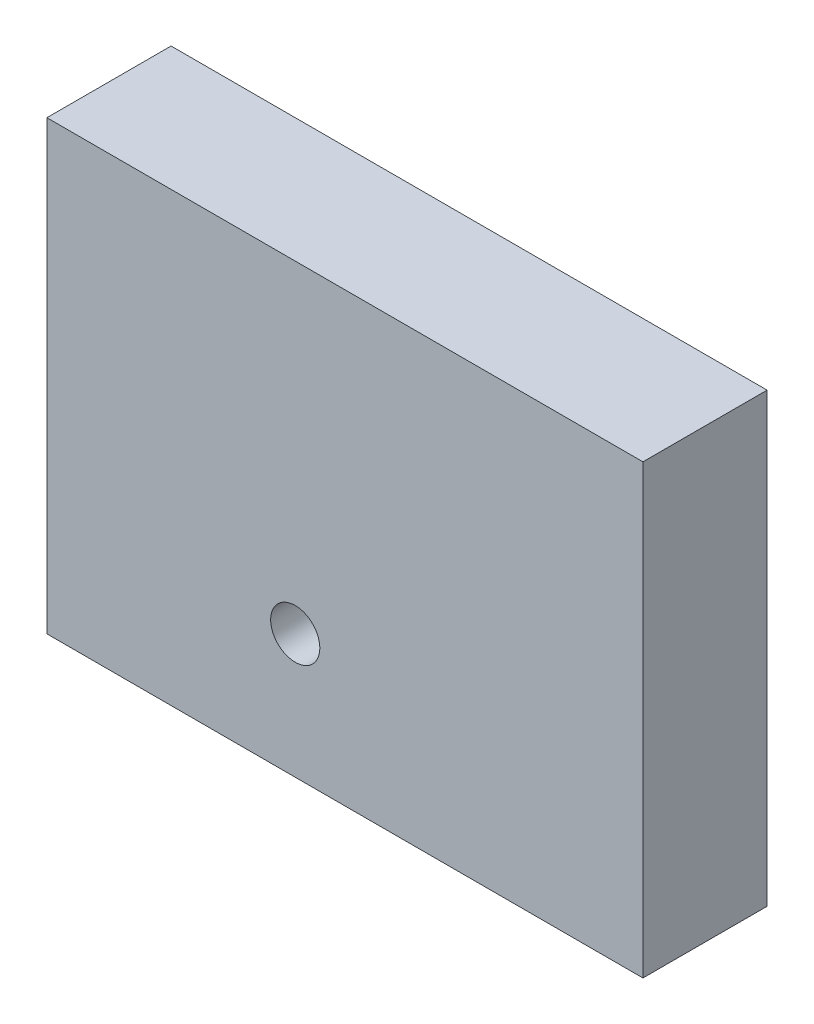
SolidWorks part; units mm, degrees
ref_plane "Ön Düzlem" through (0, 0, 0) normal (0, 0, 1) x (1, 0, 0)
ref_plane "Üst Düzlem" through (0, 0, 0) normal (0, 1, 0) x (1, 0, 0)
ref_plane "Sağ Düzlem" through (0, 0, 0) normal (1, 0, 0) x (0, 0, -1)
sketch "Çizim1" plane through (0, 0, 0) normal (0, 0, 1) x (1, 0, 0)
  line L1 (-24, -18) -> (24, -18)
  line L2 (-24, -18) -> (-24, 18)
  line L3 (-24, 18) -> (24, 18)
  line L4 (24, -18) -> (24, 18)
  line L5 (-24, -18) -> (24, 18) construction
  line L6 (-24, 18) -> (24, -18) construction
  line L7 (-5.4, -9.4) -> (-2.6, -9.4)
  line L8 (-5.4, -9.4) -> (-5.4, -6.6)
  line L9 (-5.4, -6.6) -> (-2.6, -6.6)
  line L10 (-2.6, -9.4) -> (-2.6, -6.6)
  line L11 (-5.4, -9.4) -> (-2.6, -6.6) construction
  line L12 (-5.4, -6.6) -> (-2.6, -9.4) construction
  point P0 (0, 0)
  point P6 (-4, -8)
  point P13 (4.6619, -20.5911)
  point P14 (2.7015, -18)
  dimension "D1" = 36
  dimension "D2" = 48
  dimension "D3" = 2.8
  dimension "D4" = 2.8
  dimension "D5" = 20
  dimension "D6" = 10
extrude "Yükseklik-Ekstrüzyon1" add sketch "Çizim1" along normal blind 10
sketch "Çizim2" plane through (0, 0, 10) normal (0, 0, 1) x (1, 0, 0)
  circle A0 centre (-4, -8) radius 1.9799
extrude "Kes-Ekstrüzyon2" cut sketch "Çizim2" against normal blind 10
